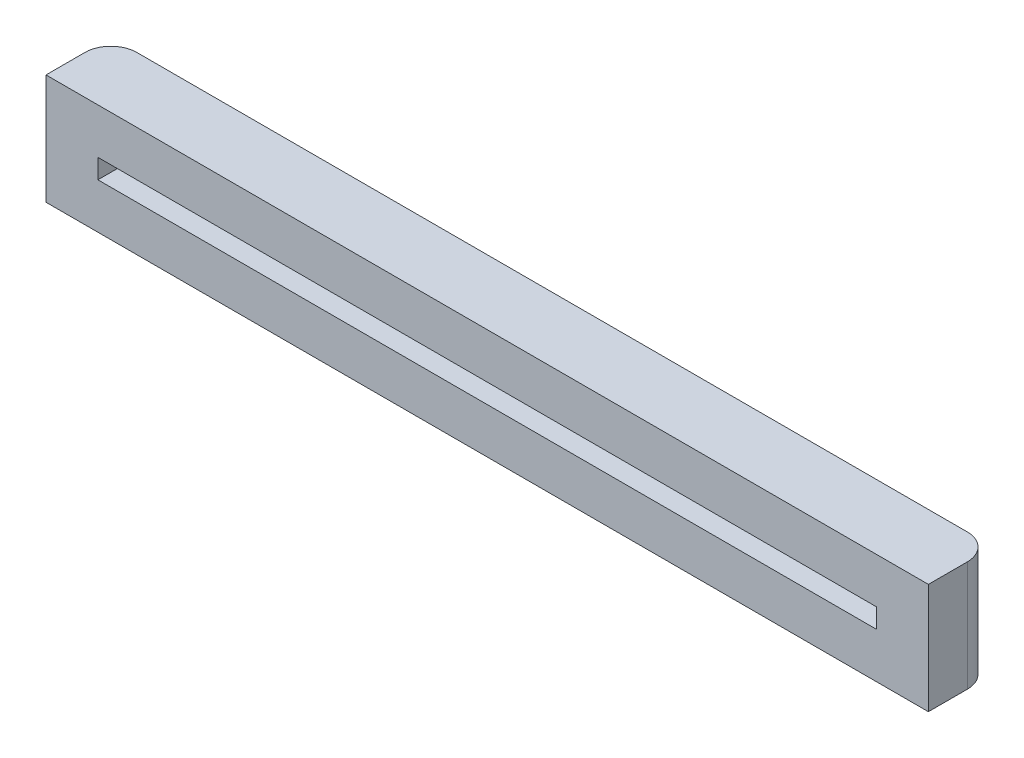
SolidWorks part; units mm, degrees
ref_plane "Front Plane" through (0, 0, 0) normal (0, 0, 1) x (1, 0, 0)
ref_plane "Top Plane" through (0, 0, 0) normal (0, 1, 0) x (1, 0, 0)
ref_plane "Right Plane" through (0, 0, 0) normal (1, 0, 0) x (0, 0, -1)
sketch "Sketch1" plane through (0, 0, 0) normal (0, 0, 1) x (1, 0, 0)
  line L1 (0, 0) -> (68, 0)
  line L2 (0, 0) -> (0, 8.5)
  line L3 (0, 8.5) -> (68, 8.5)
  line L4 (68, 0) -> (68, 8.5)
  dimension "D1" = 68
  dimension "D2" = 8.5
extrude "Boss-Extrude1" add sketch "Sketch1" along normal blind 5
sketch "Sketch2" plane through (0, 0, 5) normal (0, 0, 1) x (1, 0, 0)
  line L0 (68, 8.5) -> (0, 8.5) construction
  line L1 (4, 5) -> (64, 5)
  line L2 (4, 5) -> (4, 3.5)
  line L3 (4, 3.5) -> (64, 3.5)
  line L4 (64, 5) -> (64, 3.5)
  line L5 (0, 8.5) -> (0, 0) construction
  dimension "D1" = 60
  dimension "D2" = 1.5
  dimension "D3" = 3.5
  dimension "D4" = 4
extrude "Cut-Extrude1" cut sketch "Sketch2" against normal blind 3
fillet "Fillet1" radius 2 2 edges at (68, 4.25, 0) (0, 4.25, 0)
